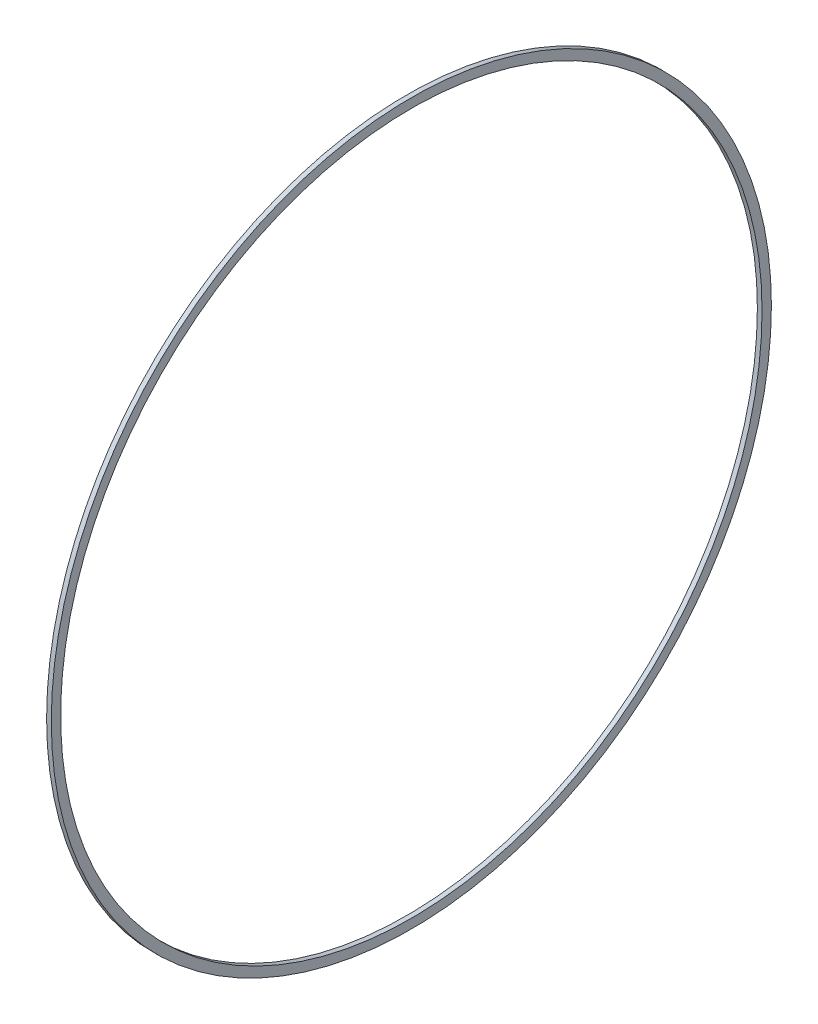
SolidWorks part; units mm, degrees
ref_plane "Front Plane" through (0, 0, 0) normal (0, 0, 1) x (1, 0, 0)
ref_plane "Top Plane" through (0, 0, 0) normal (0, 1, 0) x (1, 0, 0)
ref_plane "Right Plane" through (0, 0, 0) normal (1, 0, 0) x (0, 0, -1)
sketch "Sketch1" plane through (0, 0, 0) normal (1, 0, 0) x (0, 0, -1)
  circle A0 centre (0, 0) radius 750
  circle A1 centre (0, 0) radius 770
  dimension "D2" = 1500
  dimension "D3" = 20
  dimension "D1" = 20
extrude "Boss-Extrude1" add sketch "Sketch1" along normal blind 10
